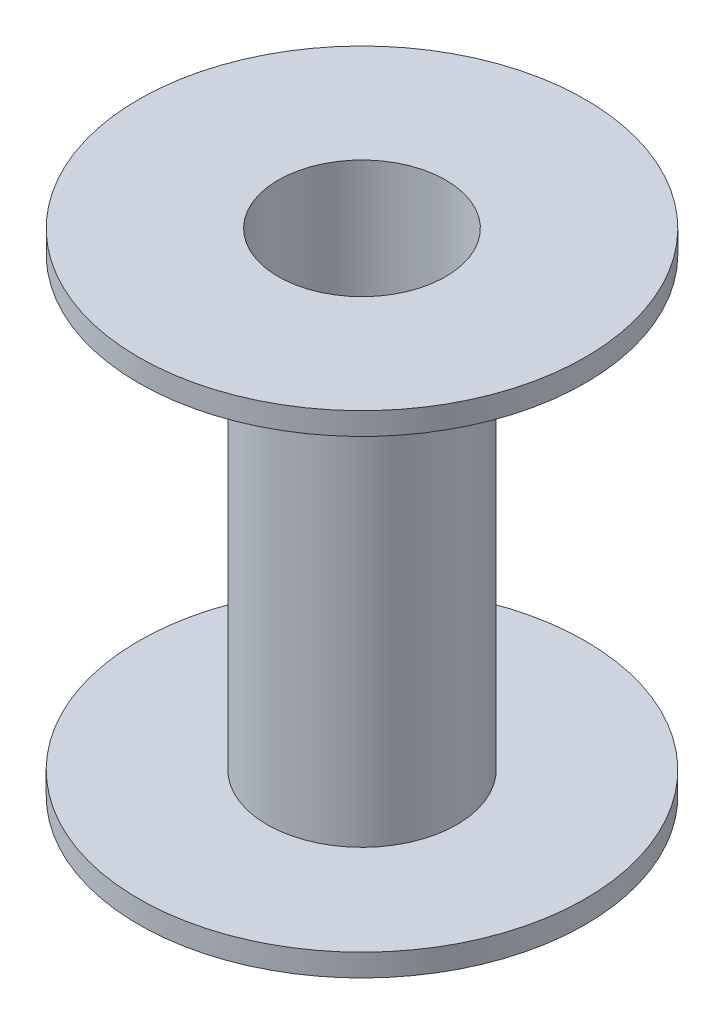
SolidWorks part; units mm, degrees
ref_plane "Front Plane" through (0, 0, 0) normal (0, 0, 1) x (1, 0, 0)
ref_plane "Top Plane" through (0, 0, 0) normal (0, 1, 0) x (1, 0, 0)
ref_plane "Right Plane" through (0, 0, 0) normal (1, 0, 0) x (0, 0, -1)
sketch "Sketch3" plane through (0, 0, 0) normal (0, 1, 0) x (1, 0, 0)
  circle A0 centre (0, 0) radius 4.25
  circle A1 centre (0, 0) radius 3.75
  dimension "D1" = 7.5
  dimension "D2" = 8.5
extrude "Boss-Extrude1" add sketch "Sketch3" along normal blind 20
sketch "Sketch21" plane through (0, 20, 0) normal (0, 1, 0) x (1, 0, 0)
  circle A0 centre (0, 0) radius 10
  dimension "D1" = 20
extrude "Boss-Extrude2" add sketch "Sketch21" along normal blind 1
sketch "Sketch29" plane through (0, 21, 0) normal (0, 1, 0) x (1, 0, 0)
  circle A0 centre (0, 0) radius 1.75
  circle A1 centre (0, 0) radius 3
  dimension "D1" = 6
  dimension "D2" = 3.5
extrude "Cut-Extrude6" cut sketch "Sketch29" against normal blind 8.3 contours A0
sketch "Sketch33" plane through (0, 0, 0) normal (0, -1, 0) x (1, 0, 0)
  circle A0 centre (0, 0) radius 10
  dimension "D1" = 20
extrude "Boss-Extrude5" add sketch "Sketch33" along normal blind 1
sketch "Sketch35" plane through (0, -1, 0) normal (0, -1, 0) x (1, 0, 0)
  circle A0 centre (0, 0) radius 3.75
  dimension "D1" = 7.5
extrude "Cut-Extrude8" cut sketch "Sketch35" against normal through all
